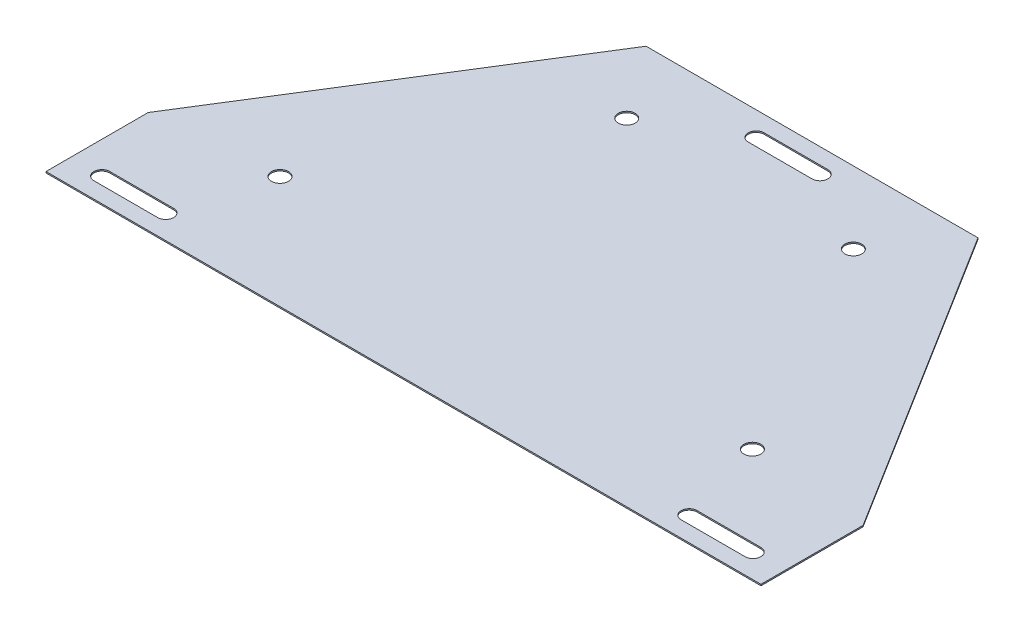
SolidWorks part; units mm, degrees
material "Alloy Steel"
ref_plane "Front Plane" through (0, 0, 0) normal (0, 0, 1) x (1, 0, 0)
ref_plane "Top Plane" through (0, 0, 0) normal (0, 1, 0) x (1, 0, 0)
ref_plane "Right Plane" through (0, 0, 0) normal (1, 0, 0) x (0, 0, -1)
sketch "Sketch1" plane through (0, 0, 0) normal (0, 1, 0) x (1, 0, 0)
  line L0 (-838.2, 0) -> (838.2, 0)
  line L1 (838.2, 0) -> (330.2, 812.8)
  line L2 (330.2, 812.8) -> (-330.2, 812.8)
  line L3 (-330.2, 812.8) -> (-838.2, 0)
  line L4 (-711.2, 203.2) -> (-711.2, 0)
  line L5 (0, 812.8) -> (0, 0) construction
  line L6 (711.2, 203.2) -> (711.2, 0)
  point P5 (0, 812.8)
  dimension "D1" = 1676.4
  dimension "D2" = 660.4
  dimension "D3" = 812.8
  dimension "D4" = 127
extrude "Boss-Extrude1" add sketch "Sketch1" along normal blind 2.6568 contours L5 L2 L3 L4 L0 | L2 L5 L0 L6 L1
sketch "Sketch2" plane through (0, 2.6568, 0) normal (0, 1, 0) x (1, 0, 0)
  line L0 (-63.5, 765.175) -> (63.5, 765.175) construction
  line L1 (-63.5, 781.05) -> (63.5, 781.05)
  line L2 (-63.5, 749.3) -> (63.5, 749.3)
  line L3 (-647.7, 47.625) -> (-520.7, 47.625) construction
  line L4 (-647.7, 63.5) -> (-520.7, 63.5)
  line L5 (-647.7, 31.75) -> (-520.7, 31.75)
  line L6 (520.7, 47.625) -> (647.7, 47.625) construction
  line L7 (520.7, 63.5) -> (647.7, 63.5)
  line L8 (520.7, 31.75) -> (647.7, 31.75)
  line L9 (0, 0) -> (0, 812.8) construction
  line L10 (330.2, 812.8) -> (-330.2, 812.8) construction
  line L11 (-711.2, 0) -> (711.2, 0) construction
  arc A0 (-63.5, 781.05) -> (-63.5, 749.3) centre (-63.5, 765.175) ccw
  arc A1 (63.5, 749.3) -> (63.5, 781.05) centre (63.5, 765.175) ccw
  arc A2 (-647.7, 63.5) -> (-647.7, 31.75) centre (-647.7, 47.625) ccw
  arc A3 (-520.7, 31.75) -> (-520.7, 63.5) centre (-520.7, 47.625) ccw
  arc A4 (520.7, 63.5) -> (520.7, 31.75) centre (520.7, 47.625) ccw
  arc A5 (647.7, 31.75) -> (647.7, 63.5) centre (647.7, 47.625) ccw
  point P2 (0, 765.175)
  point P7 (-584.2, 47.625)
  point P14 (584.2, 47.625)
  dimension "D1" = 31.75
  dimension "D2" = 31.75
  dimension "D3" = 127
  dimension "D4" = 31.75
  dimension "D5" = 31.75
  dimension "D6" = 1168.4
  dimension "D7" = 584.2
  dimension "D8" = 31.75
extrude "Cut-Extrude1" cut sketch "Sketch2" against normal through all
sketch "Sketch3" plane through (0, 2.6568, 0) normal (0, 1, 0) x (1, 0, 0)
  line L0 (-711.2, 0) -> (711.2, 0) construction
  line L1 (0, 0) -> (0, 812.8) construction
  line L2 (330.2, 812.8) -> (-330.2, 812.8) construction
  circle A0 centre (-469.9, 224.282) radius 16.891
  circle A1 centre (-225.425, 669.5864) radius 16.891
  circle A2 centre (225.425, 669.5864) radius 16.891
  circle A3 centre (469.9, 224.282) radius 16.891
  dimension "D1" = 33.782
  dimension "D3" = 469.9
  dimension "D4" = 508
  dimension "D5" = 225.425
  dimension "D2" = 224.282
extrude "Cut-Extrude2" cut sketch "Sketch3" against normal through all
equation "\"D7@Sketch2\"=\"D6@Sketch2\"/2"
